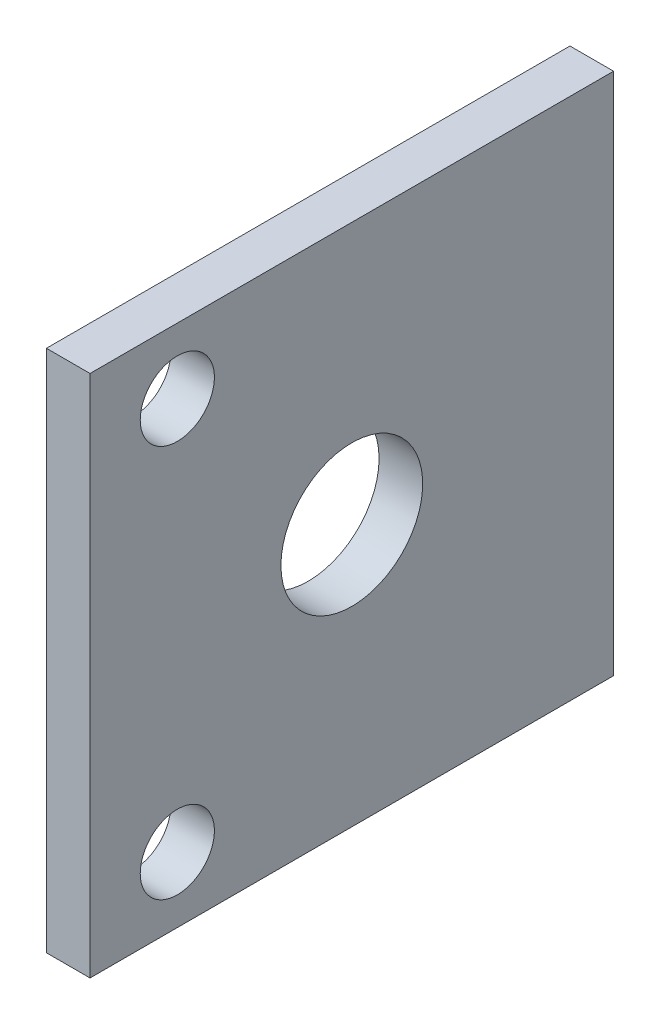
SolidWorks part; units mm, degrees
other "Preload Metal Thrust Reaction Plate"
ref_plane "Front Plane" through (0, 0, 0) normal (0, 0, 1) x (1, 0, 0)
ref_plane "Top Plane" through (0, 0, 0) normal (0, 1, 0) x (1, 0, 0)
ref_plane "Right Plane" through (0, 0, 0) normal (1, 0, 0) x (0, 0, -1)
sketch3d "Thrust plate blank sketch datum points"
  point P0 (13, -41, -31.5)
  point P1 (23, -41, -31.5)
  point P2 (13, -31, -31.5)
ref_plane "Thrust plate blank sketch plane" through (0, 0, -31.5) normal (0, 0, 1) x (1, 0, 0)
sketch "Thrust plate blank sketch" plane through (0, 0, -31.5) normal (0, 0, 1) x (1, 0, 0)
  line L0 (13, -41) -> (15, -41)
  line L1 (15, -41) -> (15, -17)
  line L2 (15, -17) -> (13, -17)
  line L3 (13, -17) -> (13, -41)
extrude "Thrust plate blank" add sketch "Thrust plate blank sketch" along normal blind 24 separate body
sketch3d "Screw running clearance sketch datum points"
  point P0 (12.9, -29, -19.5)
  point P1 (12.9, -19, -19.5)
  point P2 (12.9, -29, -9.5)
ref_plane "Screw running clearance sketch plane" through (12.9, 0, 0) normal (1, 0, 0) x (0, 0, -1)
sketch "Screw running clearance sketch" plane through (12.9, 0, 0) normal (1, 0, 0) x (0, 0, -1)
  circle A0 centre (19.5, -29) radius 3.25
extrude "Screw running clearance" cut sketch "Screw running clearance sketch" along normal blind 2.2
sketch3d "M3 plate clearance 1 sketch datum points"
  point P0 (12.9, -38, -11.5)
  point P1 (12.9, -28, -11.5)
  point P2 (12.9, -38, -1.5)
ref_plane "M3 plate clearance 1 sketch plane" through (12.9, 0, 0) normal (1, 0, 0) x (0, 0, -1)
sketch "M3 plate clearance 1 sketch" plane through (12.9, 0, 0) normal (1, 0, 0) x (0, 0, -1)
  circle A0 centre (11.5, -38) radius 1.7
extrude "M3 plate clearance 1" cut sketch "M3 plate clearance 1 sketch" along normal blind 2.2
sketch3d "M3 plate clearance 2 sketch datum points"
  point P0 (12.9, -20, -11.5)
  point P1 (12.9, -10, -11.5)
  point P2 (12.9, -20, -1.5)
ref_plane "M3 plate clearance 2 sketch plane" through (12.9, 0, 0) normal (1, 0, 0) x (0, 0, -1)
sketch "M3 plate clearance 2 sketch" plane through (12.9, 0, 0) normal (1, 0, 0) x (0, 0, -1)
  circle A0 centre (11.5, -20) radius 1.7
extrude "M3 plate clearance 2" cut sketch "M3 plate clearance 2 sketch" along normal blind 2.2
